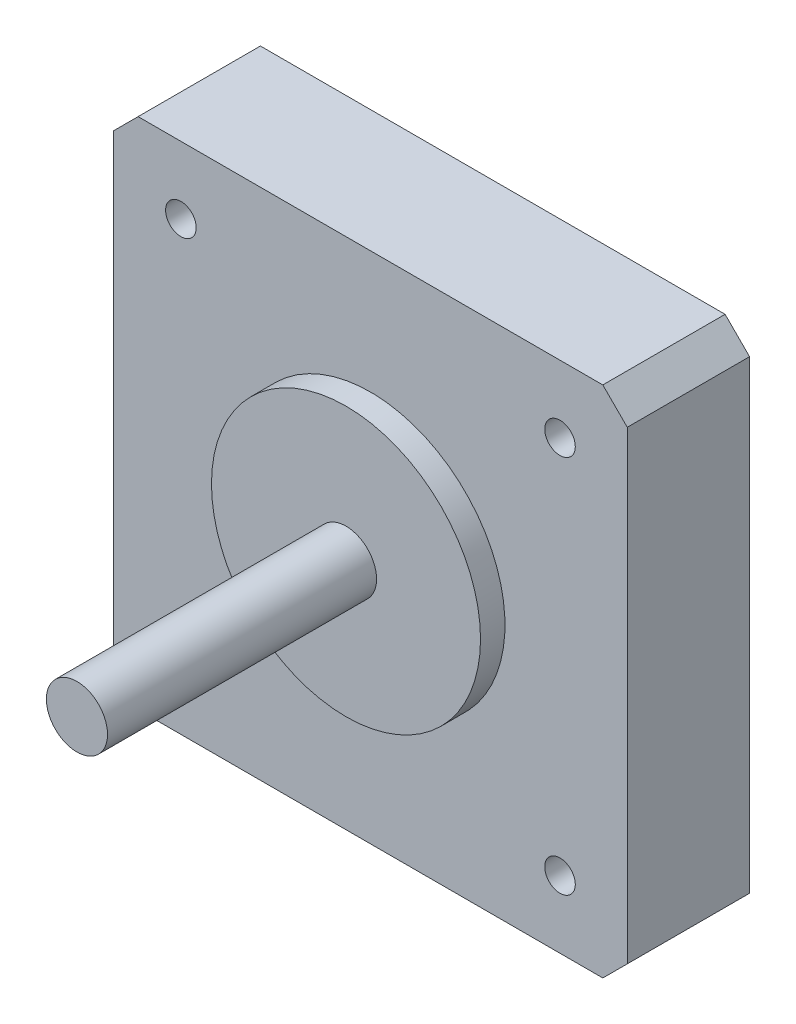
SolidWorks part; units mm, degrees
ref_plane "前视基准面" through (0, 0, 0) normal (0, 0, 1) x (1, 0, 0)
ref_plane "上视基准面" through (0, 0, 0) normal (0, 1, 0) x (1, 0, 0)
ref_plane "右视基准面" through (0, 0, 0) normal (1, 0, 0) x (0, 0, -1)
sketch "草图1" plane through (0, 0, 0) normal (0, 0, 1) x (1, 0, 0)
  line L1 (-21, -21) -> (21, -21)
  line L2 (-21, -21) -> (-21, 21)
  line L3 (-21, 21) -> (21, 21)
  line L4 (21, -21) -> (21, 21)
  line L5 (-21, -21) -> (21, 21) construction
  line L6 (-21, 21) -> (21, -21) construction
  point P0 (0, 0)
  dimension "D1" = 42
  dimension "D2" = 42
extrude "凸台-拉伸1" add sketch "草图1" along normal blind 10
sketch "草图2" plane through (0, 0, 10) normal (0, 0, 1) x (1, 0, 0)
  circle A0 centre (0, 0) radius 2.5
  dimension "D1" = 5
extrude "凸台-拉伸2" add sketch "草图2" along normal blind 24
sketch "草图3" plane through (0, 0, 10) normal (0, 0, 1) x (1, 0, 0)
  circle A0 centre (0, 0) radius 11
  dimension "D1" = 22
extrude "凸台-拉伸3" add sketch "草图3" along normal blind 2
chamfer "倒角1" distance 2 angle 45 4 edges at (-21, -21, 5) (21, -21, 5) (-21, 21, 5) (21, 21, 5)
hole_wizard "M3 螺纹孔1" positions "草图6" profile "草图5" tap size "M3" standard "GB"
sketch "草图6" plane through (0, 0, 10) normal (0, 0, 1) x (1, 0, 0)
  circle A0 centre (0, 0) radius 2.5 construction
  point P0 (15.5, 15.5)
  dimension "D2" = 15.5
  dimension "D1" = 15.5
sketch "草图5" plane through (15.5, 15.5, 10) normal (1, 0, 0) x (0, -1, 0)
  line L0 (0, 0) -> (0, 8.2511)
  line L1 (0, 8.2511) -> (1.25, 7.5)
  line L2 (1.25, 7.5) -> (1.25, 0)
  line L5 (1.25, 0) -> (0, 0)
  line L10 (0, 8.2511) -> (-1.25, 7.5) construction
  line L11 (0, -6.35) -> (0, 107.95) construction
  dimension "螺纹孔钻头直径" = 2.5
  dimension "螺纹孔钻头深度" = 7.5
  dimension "导头角度" = 118
cosmetic thread "孔螺蚊线1" parameters "D1"=6, "D2"=3
pattern_circular "阵列(圆周)2" count 4 every 90 about axis through (0, 0, 0) along (0, 0, 1) of "M3 螺纹孔1"
